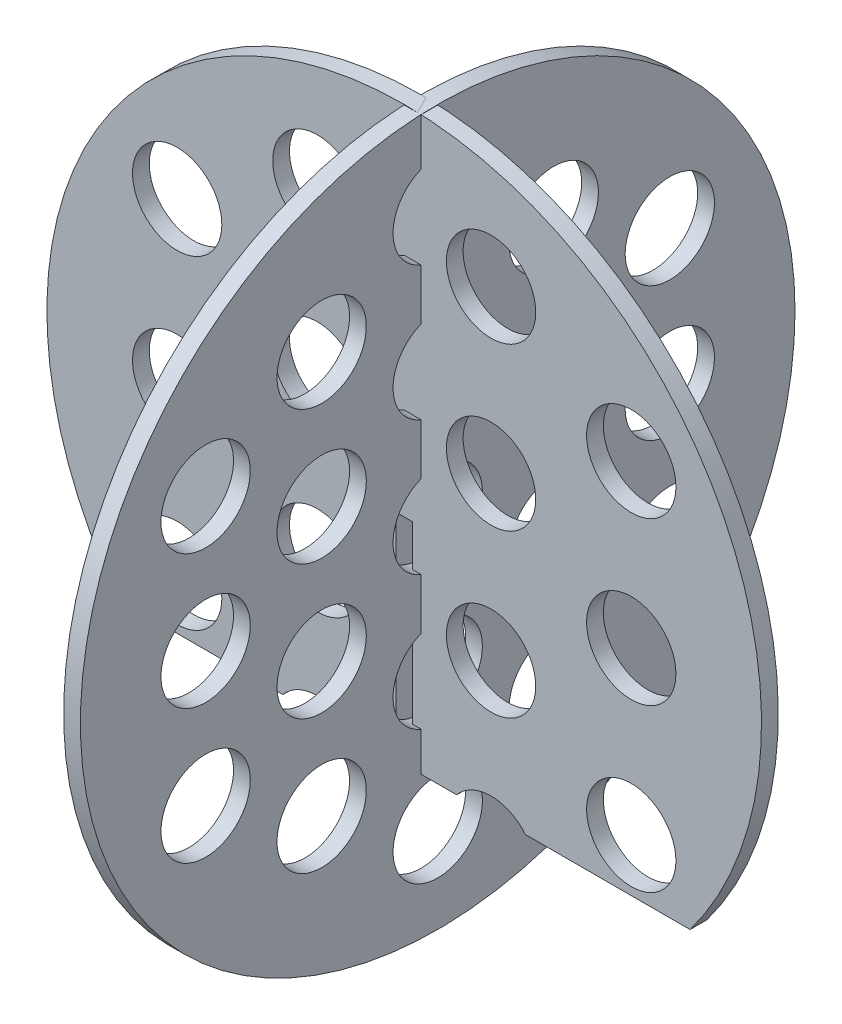
SolidWorks part; units mm, degrees
ref_plane "Front Plane" through (0, 0, 0) normal (0, 0, 1) x (1, 0, 0)
ref_plane "Top Plane" through (0, 0, 0) normal (0, 1, 0) x (1, 0, 0)
ref_plane "Right Plane" through (0, 0, 0) normal (1, 0, 0) x (0, 0, -1)
sketch "Sketch1" plane through (0, 0, 0) normal (1, 0, 0) x (0, 0, -1)
  line L0 (0, 12) -> (0, 0) construction
  line L1 (0, 12) -> (10.3923, 18) construction
  line L2 (10.3923, 18) -> (10.3923, 6) construction
  line L3 (10.3923, 6) -> (0, 12) construction
  line L4 (10.3923, 6) -> (0, 0) construction
  line L5 (0, 12) -> (0, 24) construction
  circle A0 centre (0, 0) radius 32
  circle A1 centre (0, 0) radius 4
  circle A2 centre (0, 12) radius 4
  circle A3 centre (10.3923, 6) radius 4
  circle A4 centre (10.3923, -6) radius 4
  circle A5 centre (0, -12) radius 4
  circle A6 centre (-10.3923, -6) radius 4
  circle A7 centre (-10.3923, 6) radius 4
  circle A8 centre (10.3923, 18) radius 4
  circle A9 centre (20.7846, 0) radius 4
  circle A10 centre (20.7846, 12) radius 4
  circle A11 centre (0, 24) radius 4
  circle A12 centre (20.7846, -12) radius 4
  circle A13 centre (10.3923, -18) radius 4
  circle A14 centre (0, -24) radius 4
  circle A15 centre (-10.3923, -18) radius 4
  circle A16 centre (-20.7846, -12) radius 4
  circle A17 centre (-20.7846, 0) radius 4
  circle A18 centre (-20.7846, 12) radius 4
  circle A19 centre (-10.3923, 18) radius 4
  point P19 (0, 0)
  point P25 (-13.2582, -24.7801)
  point P26 (0, 0)
  point P44 (0, 0)
  dimension "D1" = 64
  dimension "D2" = 8
  dimension "D3" = 12
  dimension "D5" = 3
  dimension "D4" = 6
extrude "Boss-Extrude1" add sketch "Sketch1" along normal blind 1.5
sketch "Sketch2" plane through (0, 0, 0) normal (0, 0, 1) x (1, 0, 0)
  line L5 (0, 32) -> (0, -32) construction
  line L6 (-0.75, -31.9912) -> (-0.75, 0)
  line L7 (0.75, 31.9912) -> (0.75, 21.75) construction
  line L8 (7.7761, -7.25) -> (7.7761, 7.25) construction
  line L9 (7.7761, 7.25) -> (20.3334, 0) construction
  line L10 (7.7761, 21.75) -> (20.3334, 14.5) construction
  line L11 (20.3334, 14.5) -> (7.7761, 7.25) construction
  line L12 (7.7761, 7.25) -> (7.7761, 21.75) construction
  line L13 (20.3334, 0) -> (7.7761, -7.25) construction
  line L14 (7.7761, -21.75) -> (7.7761, -7.25) construction
  line L15 (20.3334, -14.5) -> (7.7761, -21.75) construction
  line L16 (7.7761, -7.25) -> (20.3334, -14.5) construction
  line L17 (20.3334, 0) -> (20.3334, -14.5) construction
  line L18 (20.3334, 14.5) -> (20.3334, 0) construction
  line L19 (3.7761, 21.75) -> (0.75, 21.75) construction
  line L20 (23.5902, 16.8224) -> (26.0539, 18.5794) construction
  line L21 (26.0539, 18.5794) -> (16.4898, 31.9912) construction
  line L22 (-0.75, 0) -> (0.75, 0)
  line L23 (0.75, 0) -> (0.75, -31.9912)
  circle A0 centre (0, 0) radius 32
  circle A20 centre (7.7761, 21.75) radius 4
  circle A21 centre (7.7761, 7.25) radius 4
  circle A22 centre (7.7761, -7.25) radius 4
  circle A23 centre (7.7761, -21.75) radius 4
  circle A24 centre (20.3334, 14.5) radius 4
  circle A25 centre (20.3334, 0) radius 4
  circle A26 centre (20.3334, -14.5) radius 4
  circle A28 centre (-7.7761, -21.75) radius 4
  circle A30 centre (-7.7761, -7.25) radius 4
  circle A31 centre (-20.3334, -14.5) radius 4
  circle A32 centre (-20.3334, 0) radius 4
  circle A33 centre (-20.3334, 14.5) radius 4
  circle A34 centre (-7.7761, 7.25) radius 4
  circle A35 centre (-7.7761, 21.75) radius 4
  point P19 (0, 0)
  point P44 (0, 0)
  dimension "D1" = 64
  dimension "D6" = 0.75
  dimension "D9" = 8
  dimension "D8" = 14.5
  dimension "D7" = 0.75
extrude "Boss-Extrude2" add sketch "Sketch2" along normal blind 1.5 separate body contours L23 A0 L6 L22 A34 A32 A30 A20 A21 A22 A23 A24 A25 A26 A28 A31 A33 A35
sketch "Sketch3" plane through (0, 0, 1.5) normal (0, 0, 1) x (1, 0, 0)
  line L0 (-50, -32) -> (50, -32)
  line L1 (-50, -19.2) -> (50, -19.2)
  line L2 (-50, -19.2) -> (-50, -32)
  line L3 (50, -19.2) -> (50, -32)
  arc A1 (0.75, -31.9912) -> (-0.75, -31.9912) centre (0, 0) ccw construction
  point P7 (0, -19.2)
  dimension "D1" = 0
  dimension "D2" = 12.8
  dimension "D3" = 100
extrude "Cut-Extrude2" cut sketch "Sketch3" against normal through all both and the other way through all
